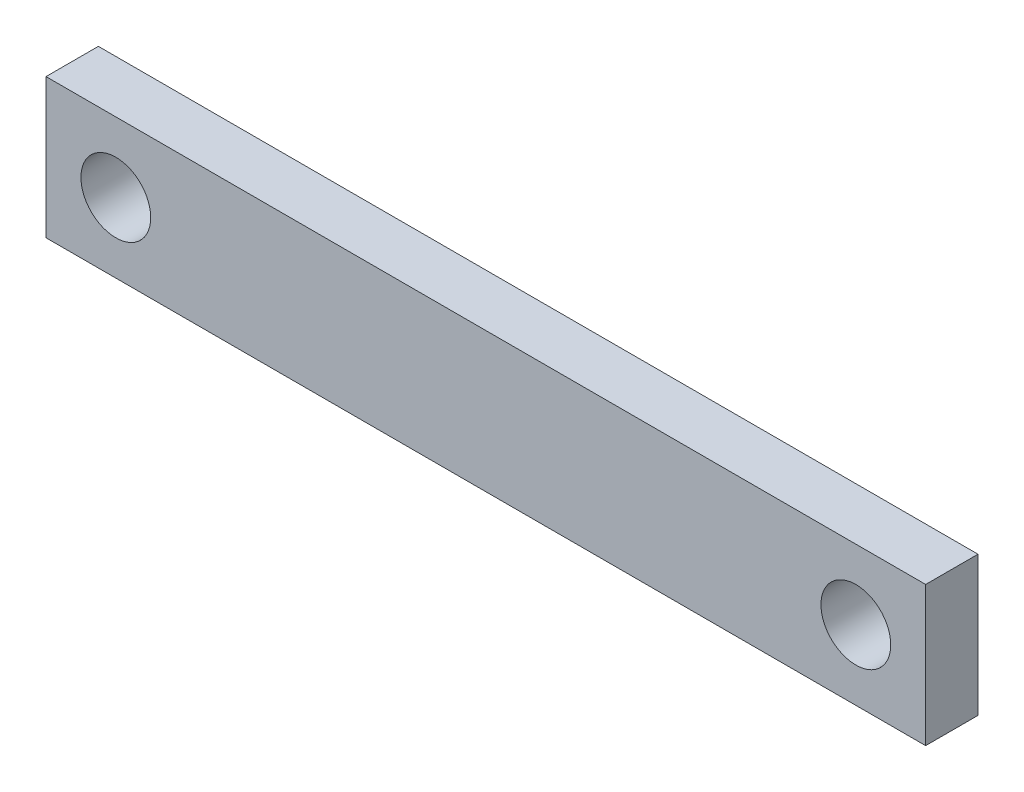
SolidWorks part; units mm, degrees
material "Plain Carbon Steel"
ref_plane "Front Plane" through (0, 0, 0) normal (0, 0, 1) x (1, 0, 0)
ref_plane "Top Plane" through (0, 0, 0) normal (0, 1, 0) x (1, 0, 0)
ref_plane "Right Plane" through (0, 0, 0) normal (1, 0, 0) x (0, 0, -1)
sketch "Sketch1" plane through (0, 0, 0) normal (0, 0, 1) x (1, 0, 0)
  line L1 (0, 0) -> (177.8, 0)
  line L2 (0, 0) -> (0, 25.4)
  line L3 (0, 25.4) -> (177.8, 25.4)
  line L4 (177.8, 0) -> (177.8, 25.4)
  dimension "D1" = 177.8
  dimension "D2" = 25.4
extrude "Boss-Extrude1" add sketch "Sketch1" along normal blind 9.525
hole_wizard "1/2 (0.5) Diameter Hole1" positions "Sketch2" profile "Sketch3" hole size "1/2" standard "ANSI Inch" end condition through all
sketch "Sketch2" plane through (0, 0, 9.525) normal (0, 0, 1) x (1, 0, 0)
  line L0 (177.8, 12.7) -> (0, 12.7) construction
  line L1 (177.8, 0) -> (177.8, 25.4) construction
  line L2 (0, 25.4) -> (0, 0) construction
  line L3 (88.9, 0) -> (88.9, 25.4) construction
  line L4 (0, 0) -> (177.8, 0) construction
  line L5 (177.8, 25.4) -> (0, 25.4) construction
  line L6 (0, 25.4) -> (0, 0) construction
  point P2 (12.7, 12.7)
  point P23 (147.32, 12.7)
  dimension "D1" = 12.7
  dimension "D2" = 134.62
sketch "Sketch3" plane through (12.7, 12.7, 9.525) normal (1, 0, 0) x (0, -1, 0)
  line L0 (0, 0) -> (0, 9.525)
  line L1 (0, 9.525) -> (6.35, 9.525)
  line L2 (6.35, 9.525) -> (6.35, 0)
  line L5 (6.35, 0) -> (0, 0)
  line L11 (0, -6.35) -> (0, 107.95) construction
  dimension "Thru Hole Dia." = 12.7
  dimension "Thru Hole Depth" = 9.525
sketch "Sketch5" plane through (0, 0, 9.525) normal (0, 0, 1) x (1, 0, 0)
  line L0 (20.8539, 28.7029) -> (28.7029, 4.5461) construction
  line L1 (20.8539, 28.7029) -> (-69.7342, -0.7309) construction
  line L2 (28.7029, 4.5461) -> (-61.8852, -24.8878) construction
  line L3 (-69.7342, -0.7309) -> (-61.8852, -24.8878) construction
  line L4 (13.208, 25.4) -> (0, 21.4191)
  line L5 (177.8, 25.4) -> (0, 25.4) construction
  line L6 (0, 25.4) -> (0, 0) construction
  line L7 (0, 21.4191) -> (0, 25.4)
  line L8 (0, 25.4) -> (13.208, 25.4)
  line L9 (0, 0) -> (177.8, 0) construction
  circle A1 centre (12.7, 12.7) radius 6.35 construction
  point P0 (12.7, 12.7)
  point P18 (0, 21.9271)
  dimension "D1" = 12.7
  dimension "D2" = 12.7
  dimension "D3" = 25.4
  dimension "D4" = 95.25
  dimension "D5" = 0.508
  dimension "D6" = 18
  dimension "D7" = 0.508
extrude "Cut-Extrude1" [suppressed] cut sketch "Sketch5" against normal through all
sketch "Sketch6" plane through (0, 0, 9.525) normal (0, 0, 1) x (1, 0, 0)
  line L0 (0, 0) -> (177.8, 0) construction
  line L1 (177.8, 25.4) -> (160.02, 25.4)
  line L2 (177.8, 25.4) -> (177.8, 0)
  line L3 (177.8, 0) -> (160.02, 0)
  line L4 (160.02, 25.4) -> (160.02, 0)
  line L5 (147.32, 12.7) -> (12.7, 12.7) construction
  line L6 (80.01, 12.7) -> (80.01, 25.4) construction
  line L7 (177.8, 25.4) -> (0, 25.4) construction
extrude "Cut-Extrude2" cut sketch "Sketch6" against normal through all
